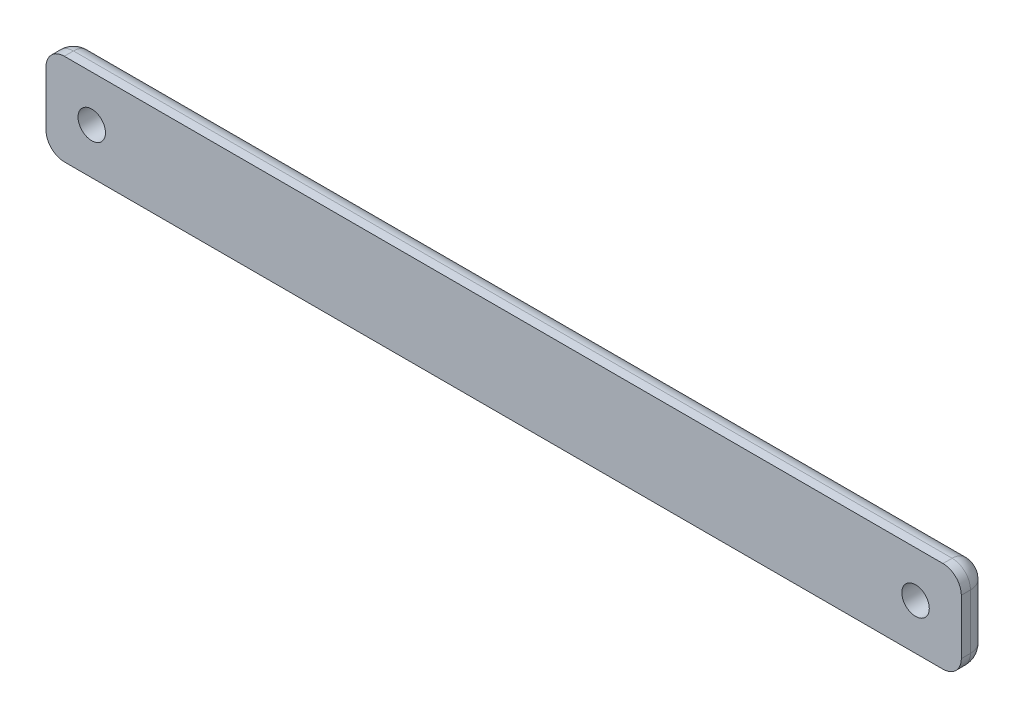
SolidWorks part; units mm, degrees
ref_plane "前视基准面" through (0, 0, 0) normal (0, 0, 1) x (1, 0, 0)
ref_plane "上视基准面" through (0, 0, 0) normal (0, 1, 0) x (1, 0, 0)
ref_plane "右视基准面" through (0, 0, 0) normal (1, 0, 0) x (0, 0, -1)
sketch "草图1" plane through (0, 0, 0) normal (0, 0, 1) x (1, 0, 0)
  line L1 (-50, 5) -> (50, 5)
  line L2 (-50, 5) -> (-50, -5)
  line L3 (-50, -5) -> (50, -5)
  line L4 (50, 5) -> (50, -5)
  line L5 (-50, 5) -> (50, -5) construction
  line L6 (-50, -5) -> (50, 5) construction
  point P0 (0, 0)
  dimension "D1" = 10
  dimension "D2" = 100
extrude "凸台-拉伸1" add sketch "草图1" along normal mid plane 3
sketch "草图2" plane through (0, 0, 1.5) normal (0, 0, 1) x (1, 0, 0)
  line L0 (-50, 5) -> (-50, -5) construction
  line L1 (50, 5) -> (-50, 5) construction
  line L2 (50, -5) -> (50, 5) construction
  circle A0 centre (-45, 0) radius 1.5
  circle A1 centre (45, 0) radius 1.5
  dimension "D1" = 5
  dimension "D2" = 5
  dimension "D3" = 5
  dimension "D4" = 5
extrude "切除-拉伸1" cut sketch "草图2" against normal blind 10
fillet "圆角1" radius 2 8 edges at (50, -5, 0) (-50, -5, 0) (-50, 5, 0) (50, 5, 0) (50, 0, -1.5) (0, -5, -1.5) (-50, 0, -1.5) (0, 5, -1.5)
